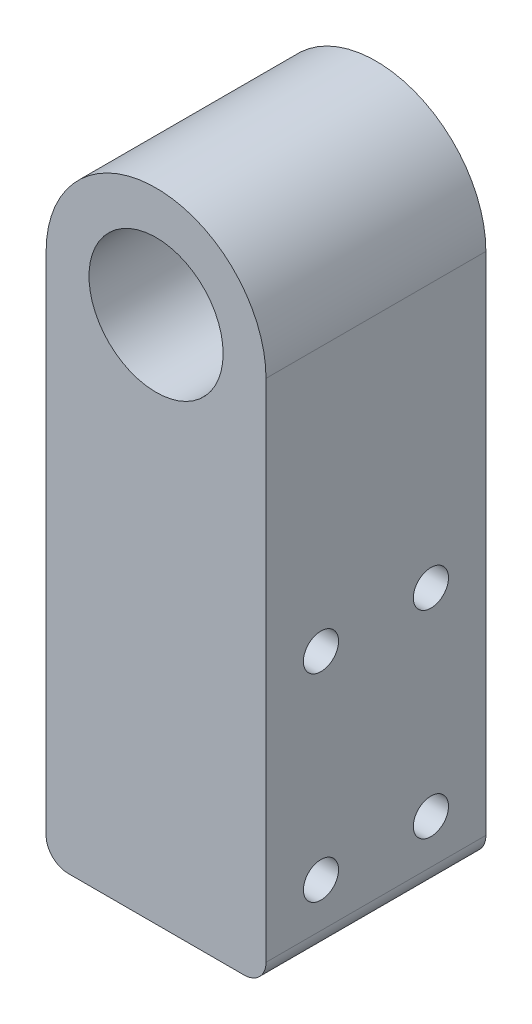
SolidWorks part; units mm, degrees
material "POM"
ref_plane "前视基准面" through (0, 0, 0) normal (0, 0, 1) x (1, 0, 0)
ref_plane "上视基准面" through (0, 0, 0) normal (0, 1, 0) x (1, 0, 0)
ref_plane "右视基准面" through (0, 0, 0) normal (1, 0, 0) x (0, 0, -1)
sketch "草图1" plane through (0, 0, 0) normal (0, 0, 1) x (1, 0, 0)
  line L0 (10, 0) -> (10, 30) construction
  line L1 (0, 0) -> (20, 0)
  line L2 (0, 0) -> (0, 30)
  line L3 (0, 30) -> (20, 30) construction
  line L4 (20, 0) -> (20, 30)
  line L5 (10, 48) -> (10, 30) construction
  line L6 (0, 30) -> (0, 48)
  line L9 (20, 30) -> (20, 48)
  circle A1 centre (10, 48) radius 6.1
  arc A2 (20, 48) -> (0, 48) centre (10, 48) ccw
  dimension "D4" = 12.2
  dimension "D5" = 20
  dimension "D1" = 30
  dimension "D2" = 20
  dimension "D3" = 18
extrude "凸台-拉伸1" add sketch "草图1" along normal blind 20
sketch "草图2" plane through (20, 0, 0) normal (1, 0, 0) x (0, 0, -1)
  line L0 (-10, 58) -> (-10, 0) construction
  line L2 (-20, 0) -> (0, 0) construction
  line L3 (-20, 15) -> (0, 15) construction
  line L4 (-20, 0) -> (-20, 48) construction
  line L5 (0, 0) -> (0, 48) construction
  line L6 (0, 58) -> (-20, 58) construction
  circle A0 centre (-15, 24) radius 1.6
  circle A1 centre (-15, 6) radius 1.6
  circle A2 centre (-5, 6) radius 1.6
  circle A3 centre (-5, 24) radius 1.6
  dimension "D2" = 3.2
  dimension "D3" = 10
  dimension "D4" = 18
  dimension "D1" = 15
extrude "切除-拉伸1" cut sketch "草图2" against normal through all
fillet "圆角1" radius 2 2 edges at (20, 0, 10) (0, 0, 10)
